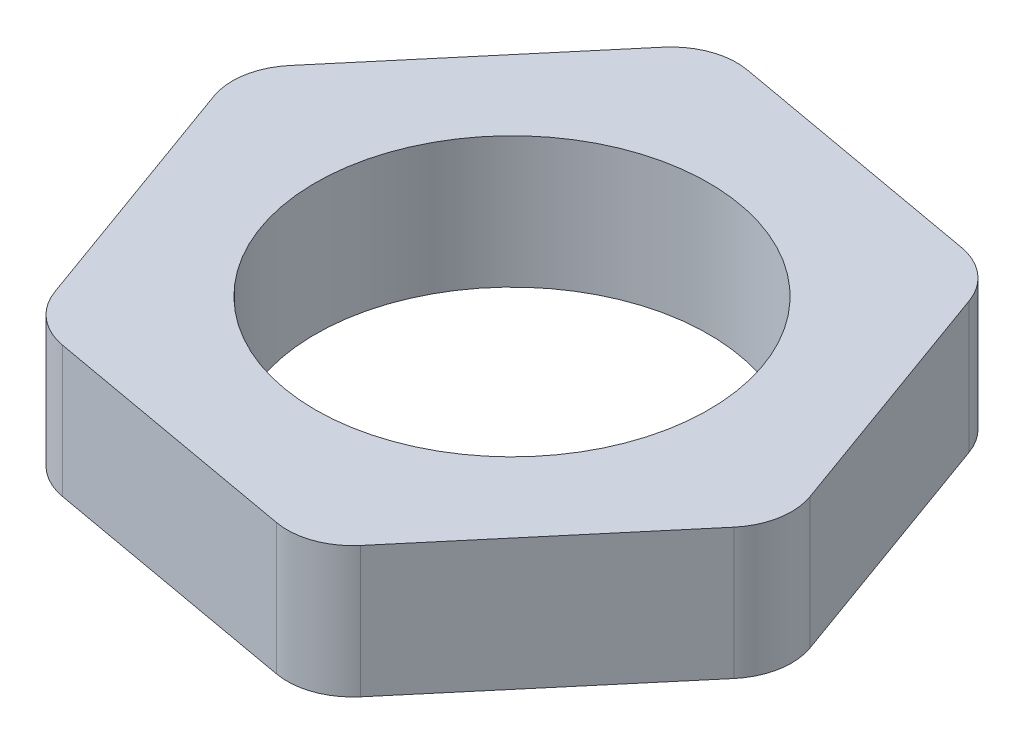
SolidWorks part; units mm, degrees
material "Plain Carbon Steel"
ref_plane "Front" through (0, 0, 0) normal (0, 0, 1) x (1, 0, 0)
ref_plane "Top" through (0, 0, 0) normal (0, 1, 0) x (1, 0, 0)
ref_plane "Right" through (0, 0, 0) normal (1, 0, 0) x (0, 0, -1)
sketch "Sketch1" plane through (0, 0, 0) normal (0, 1, 0) x (1, 0, 0)
  line L1 (-0.8825, 2.4436) -> (-2.5575, 0.4576)
  line L2 (-2.5575, 0.4576) -> (-1.675, -1.986)
  line L3 (-1.675, -1.986) -> (0.8825, -2.4436)
  line L4 (0.8825, -2.4436) -> (2.5575, -0.4576)
  line L5 (2.5575, -0.4576) -> (1.675, 1.986)
  line L6 (1.675, 1.986) -> (-0.8825, 2.4436)
  circle A0 centre (0, 0) radius 1.5
  circle A1 centre (0, 0) radius 2.25 construction
  dimension "D1" = 3
  dimension "D2" = 4.5
  dimension "D3" = 1.675
extrude "Boss-Extrude1" add sketch "Sketch1" along normal blind 1
fillet "Fillet1" radius 0.5 6 edges at (-0.8825, 0.5, -2.4436) (-2.5575, 0.5, -0.4576) (-1.675, 0.5, 1.986) (0.8825, 0.5, 2.4436) (2.5575, 0.5, 0.4576) (1.675, 0.5, -1.986)
